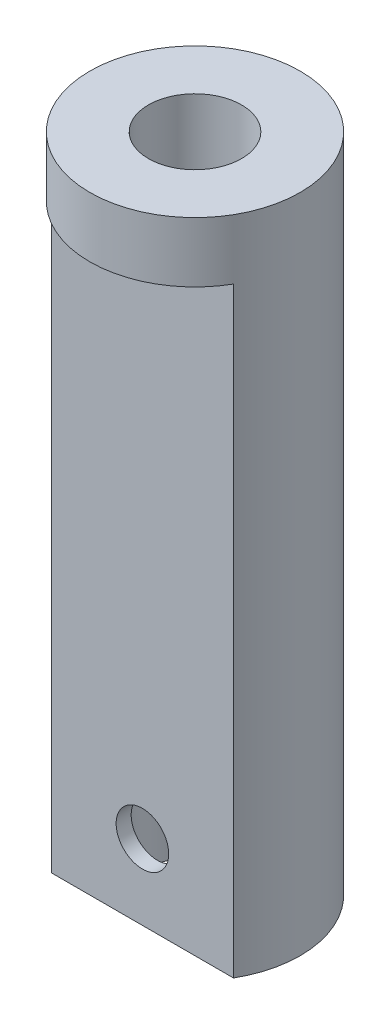
SolidWorks part; units mm, degrees
ref_plane "Ön Düzlem" through (0, 0, 0) normal (0, 0, 1) x (1, 0, 0)
ref_plane "Üst Düzlem" through (0, 0, 0) normal (0, 1, 0) x (1, 0, 0)
ref_plane "Sağ Düzlem" through (0, 0, 0) normal (1, 0, 0) x (0, 0, -1)
sketch "Çizim1" plane through (0, 0, 0) normal (0, 1, 0) x (1, 0, 0)
  line L1 (-6.0622, -3.5) -> (6.0622, -3.5)
  line L2 (-1.833, -2.5) -> (1.833, -2.5)
  arc A0 (6.0622, -3.5) -> (-6.0622, -3.5) centre (0, 0) ccw
  arc A1 (1.833, -2.5) -> (-1.833, -2.5) centre (0, 0) ccw
  dimension "D1" = 6.2
extrude "Yükseklik-Ekstrüzyon1" add sketch "Çizim1" along normal blind 30
sketch "Çizim2" plane through (0, 30, 0) normal (0, 1, 0) x (1, 0, 0)
  circle A0 centre (0, 0) radius 7
  circle A2 centre (0, 0) radius 3.1
extrude "Yükseklik-Ekstrüzyon2" add sketch "Çizim2" along normal blind 4
sketch "Çizim3" plane through (0, 0, 0) normal (0, -1, 0) x (1, 0, 0)
  line L0 (-6.0622, 3.5) -> (6.0622, 3.5)
  arc A0 (-6.0622, 3.5) -> (6.0622, 3.5) centre (0, 0) ccw
extrude "Yükseklik-Ekstrüzyon3" add sketch "Çizim3" along normal blind 10
sketch "Çizim5" plane through (0, 0, 0) normal (0, 1, 0) x (1, 0, 0)
  line L0 (-1.833, -2.5) -> (1.833, -2.5)
  arc A0 (1.833, -2.5) -> (-1.833, -2.5) centre (0, 0) ccw
extrude "Kes-Ekstrüzyon2" cut sketch "Çizim5" against normal blind 10
sketch "Çizim7" plane through (0, 0, 3.5) normal (0, 0, 1) x (1, 0, 0)
  circle A0 centre (0, -5) radius 1.75
extrude "Kes-Ekstrüzyon3" cut sketch "Çizim7" against normal blind 12
